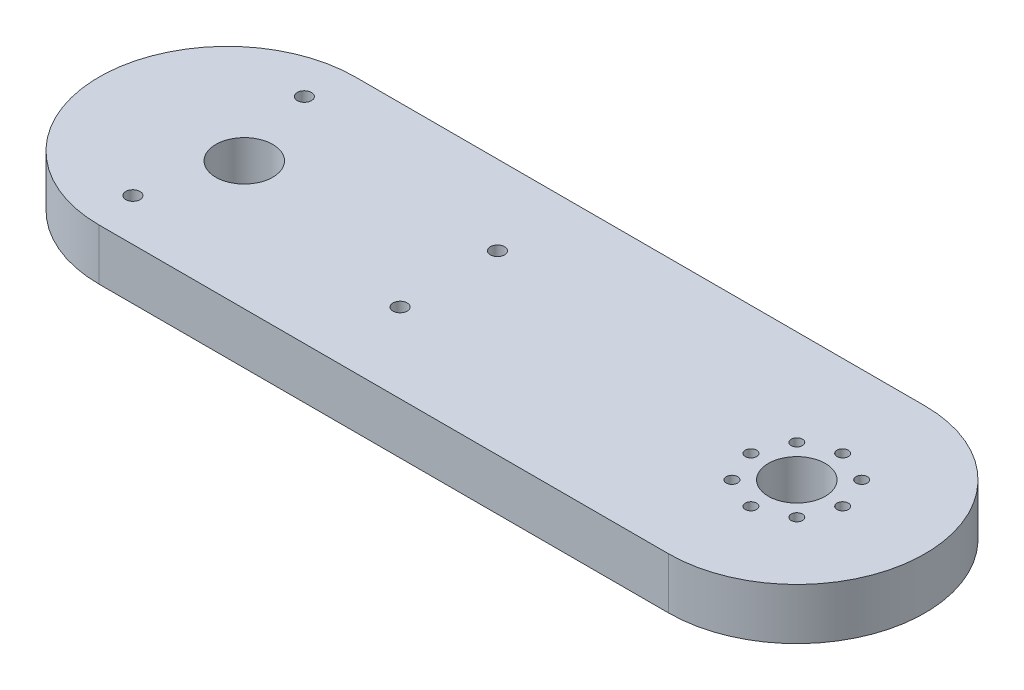
SolidWorks part; units mm, degrees
ref_plane "Front Plane" through (0, 0, 0) normal (0, 0, 1) x (1, 0, 0)
ref_plane "Top Plane" through (0, 0, 0) normal (0, 1, 0) x (1, 0, 0)
ref_plane "Right Plane" through (0, 0, 0) normal (1, 0, 0) x (0, 0, -1)
sketch "Sketch2" plane through (0, 0, 0) normal (0, 1, 0) x (1, 0, 0)
  line L0 (50, 0) -> (-50, 0) construction
  line L1 (50, -22.5) -> (-50, -22.5)
  line L2 (50, 22.5) -> (-50, 22.5)
  arc A0 (50, -22.5) -> (50, 22.5) centre (50, 0) ccw
  arc A1 (-50, 22.5) -> (-50, -22.5) centre (-50, 0) ccw
  point P2 (0, 0)
  dimension "D2" = 100
  dimension "D1" = 45
extrude "Boss-Extrude1" add sketch "Sketch2" along normal mid plane 9
sketch "Sketch3" plane through (0, 4.5, 0) normal (0, 1, 0) x (1, 0, 0)
  circle A1 centre (50, 0) radius 1.9176 construction
  arc A2 (50, -22.5) -> (50, 22.5) centre (50, 0) ccw construction
  circle A3 centre (41.95, 0) radius 0.99
  circle A17 centre (44.3078, 5.6922) radius 0.99
  circle A18 centre (50, 8.05) radius 0.99
  circle A19 centre (55.6922, 5.6922) radius 0.99
  circle A20 centre (58.05, 0) radius 0.99
  circle A21 centre (55.6922, -5.6922) radius 0.99
  circle A22 centre (50, -8.05) radius 0.99
  circle A23 centre (44.3078, -5.6922) radius 0.99
  dimension "D2" = 1.98
  dimension "D4" = 20.5824
  dimension "D1" = 8.05
  dimension "D3" = 8
extrude "Cut-Extrude1" cut sketch "Sketch3" against normal through all both and the other way through all
sketch "Sketch4" plane through (0, 4.5, 0) normal (0, 1, 0) x (1, 0, 0)
  circle A0 centre (50, 0) radius 5
  arc A1 (50, -22.5) -> (50, 22.5) centre (50, 0) ccw construction
  dimension "D1" = 10
extrude "Cut-Extrude2" cut sketch "Sketch4" against normal through all
sketch "Sketch5" plane through (0, 4.5, 0) normal (0, 1, 0) x (1, 0, 0)
  line L0 (0, 0) -> (-45.6257, 0) construction
  circle A0 centre (-51.5, -15.05) radius 1.25
  circle A1 centre (-51.5, 15.05) radius 1.25
  circle A2 centre (-11.1, 8.55) radius 1.25
  circle A3 centre (-11.1, -8.55) radius 1.25
  circle A4 centre (-47, 0) radius 5
  arc A5 (-50, 22.5) -> (-50, -22.5) centre (-50, 0) ccw construction
  dimension "D1" = 2.5
  dimension "D4" = 2.5
  dimension "D5" = 2.5
  dimension "D8" = 10
  dimension "D10" = 3
  dimension "D2" = 15.05
  dimension "D3" = 15.05
  dimension "D6" = 8.55
  dimension "D7" = 40.4
  dimension "D9" = 4.5
extrude "Cut-Extrude3" cut sketch "Sketch5" against normal through all both and the other way through all
